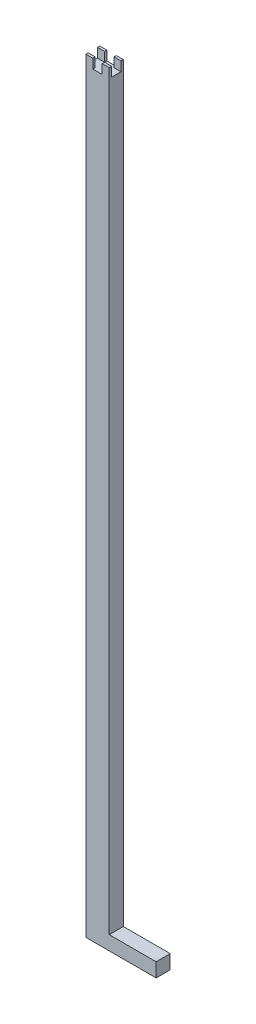
SolidWorks part; units mm, degrees
ref_plane "Front Plane" through (0, 0, 0) normal (0, 0, 1) x (1, 0, 0)
ref_plane "Top Plane" through (0, 0, 0) normal (0, 1, 0) x (1, 0, 0)
ref_plane "Right Plane" through (0, 0, 0) normal (1, 0, 0) x (0, 0, -1)
sketch "Sketch1" plane through (0, 0, 0) normal (0, 1, 0) x (1, 0, 0)
  line L1 (7.5, -1.5) -> (-7.5, -1.5)
  line L2 (7.5, -1.5) -> (7.5, 1.5)
  line L3 (7.5, 1.5) -> (-7.5, 1.5)
  line L4 (-7.5, -1.5) -> (-7.5, 1.5)
  line L5 (7.5, -1.5) -> (-7.5, 1.5) construction
  line L6 (7.5, 1.5) -> (-7.5, -1.5) construction
  point P0 (0, 0)
  dimension "D1" = 15
  dimension "D2" = 3
extrude "Boss-Extrude1" add sketch "Sketch1" along normal blind 3
ref_plane "Plane1" through (0, 3, 0) normal (0, 1, 0) x (1, 0, 0)
sketch "Sketch2" plane through (0, 3, 0) normal (0, 1, 0) x (1, 0, 0)
  line L0 (-7.5, -1.5) -> (7.5, -1.5) construction
  line L1 (-7.5, 1.5) -> (-2.5, 1.5)
  line L2 (-7.5, 1.5) -> (-7.5, -1.5)
  line L3 (-7.5, -1.5) -> (-2.5, -1.5)
  line L4 (-2.5, 1.5) -> (-2.5, -1.5)
  dimension "D1" = 5
extrude "Boss-Extrude2" add sketch "Sketch2" along normal blind 160
ref_plane "Plane2" through (0, 163, 0) normal (0, 1, 0) x (1, 0, 0)
sketch "Sketch3" plane through (0, 163, 0) normal (0, 1, 0) x (1, 0, 0)
  line L0 (-7.5, 0) -> (-6, 0) construction
  line L1 (-7.5, 1.5) -> (-7.5, -1.5) construction
  line L2 (-2.5, -1.5) -> (-2.5, 1.5) construction
  line L3 (-5, 1.5) -> (-5, 1) construction
  line L4 (-2.5, 1.5) -> (-7.5, 1.5) construction
  line L5 (-7.5, -1.5) -> (-2.5, -1.5) construction
  line L6 (-6, 1) -> (-7.5, 1)
  line L7 (-4, -1.5) -> (-6, -1.5)
  line L8 (-4, -1.5) -> (-4, -1)
  line L9 (-4, 1.5) -> (-6, 1.5)
  line L10 (-6, -1.5) -> (-6, -1)
  line L11 (-4.3333, -1) -> (-5, 0) construction
  line L12 (-4.3333, 1) -> (-5.6667, -1) construction
  line L13 (-2.5, -1) -> (-4, -1)
  line L14 (-2.5, -1) -> (-2.5, 1)
  line L15 (-2.5, 1) -> (-4, 1)
  line L16 (-7.5, -1) -> (-7.5, 1)
  line L17 (-4, -0.4) -> (-6, 0.4) construction
  line L18 (-4, 0.4) -> (-6, -0.4) construction
  line L19 (-5.6667, 1) -> (-6, 1.5) construction
  line L20 (-5, -1) -> (-5, -1.5) construction
  line L21 (-4, 1) -> (-4, 1.5)
  line L22 (-4, 0) -> (-2.5, 0) construction
  line L23 (-6, -1) -> (-7.5, -1)
  line L24 (-6, 1) -> (-6, 1.5)
  point P12 (-5, 0)
  point P17 (-5, 0)
  dimension "D1" = 2
  dimension "D2" = 2
extrude "Cut-Extrude1" cut sketch "Sketch3" against normal blind 2
